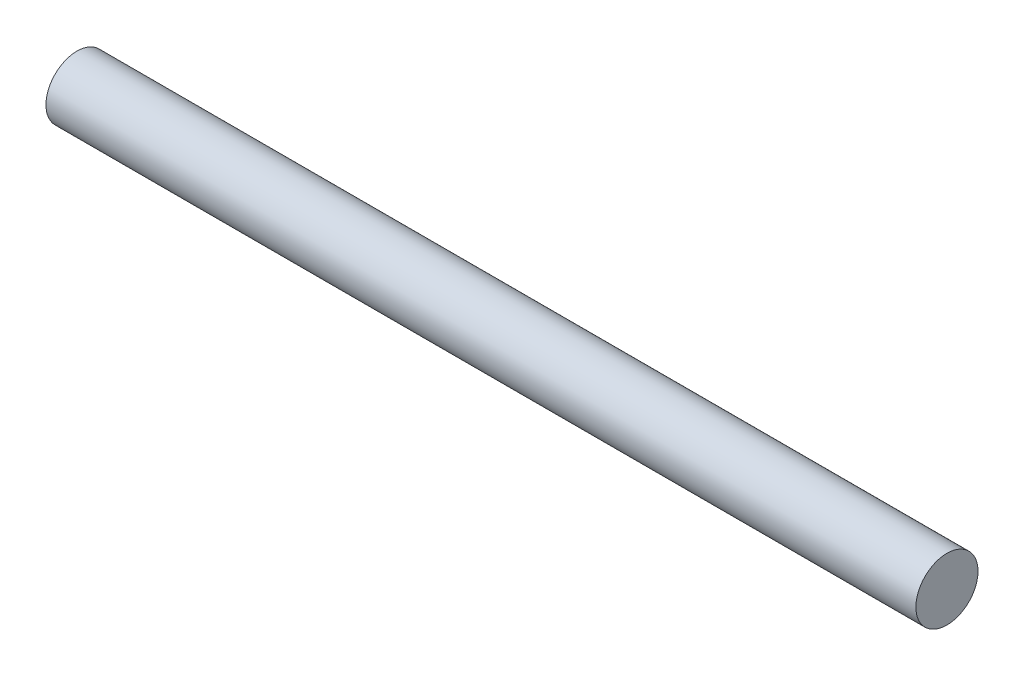
SolidWorks part; units mm, degrees
ref_plane "Front Plane" through (0, 0, 0) normal (0, 0, 1) x (1, 0, 0)
ref_plane "Top Plane" through (0, 0, 0) normal (0, 1, 0) x (1, 0, 0)
ref_plane "Right Plane" through (0, 0, 0) normal (1, 0, 0) x (0, 0, -1)
sketch "Sketch1" plane through (0, 0, 0) normal (1, 0, 0) x (0, 0, -1)
  circle A0 centre (0, 0) radius 2.5
extrude "Boss-Extrude1" add sketch "Sketch1" along normal blind 70
